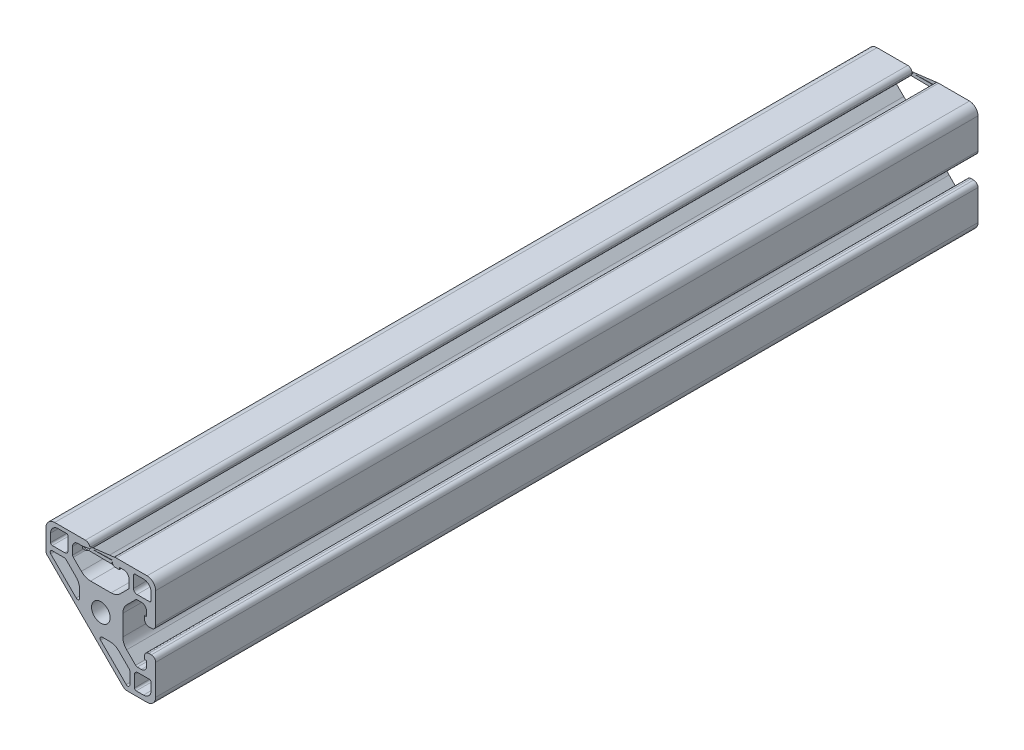
SolidWorks part; units mm, degrees
material "6105-T5 Aluminum"
ref_plane "Front Plane" through (0, 0, 0) normal (0, 0, 1) x (1, 0, 0)
ref_plane "Top Plane" through (0, 0, 0) normal (0, 1, 0) x (1, 0, 0)
ref_plane "Right Plane" through (0, 0, 0) normal (1, 0, 0) x (0, 0, -1)
sketch "Sketch1" plane through (0, 0, 0) normal (0, 0, 1) x (1, 0, 0)
  line L0 (0, 18.0022) -> (0, -18.0022) construction
  line L1 (23.2439, 0) -> (-23.2439, 0) construction
  line L2 (0, 0) -> (21.9293, 21.9293) construction
  line L4 (-22.1966, 22.1966) -> (-17.6741, 17.6741) construction
  line L5 (-17.6741, 17.6741) -> (-22.1966, 22.1966) construction
  line L6 (-17.6741, 17.6741) -> (21.6613, -21.6613) construction
  line L57 (15.55, 18.332) -> (12.565, 18.332)
  line L58 (18.35, 12.8413) -> (18.35, 15.532)
  line L59 (13.205, 12.2693) -> (17.745, 12.2693)
  line L60 (11.935, 17.702) -> (11.935, 13.5393)
  line L61 (12.8993, -18.35) -> (15.55, -18.35)
  line L62 (18.35, -15.55) -> (18.35, -12.8993)
  line L63 (17.72, -12.2693) -> (13.5393, -12.2693)
  line L64 (12.2693, -13.5393) -> (12.2693, -17.72)
  line L65 (10.5703, -17.6313) -> (10.5703, -13.2185)
  line L66 (-0.0445, -8.8513) -> (9.2729, -18.1687)
  line L67 (3.2583, -7.5539) -> (0.4929, -7.5539)
  line L68 (10.3477, -12.6811) -> (6.6079, -8.9413)
  line L69 (-9.0909, 6.7575) -> (-12.7021, 10.3687)
  line L70 (-13.3072, 10.6193) -> (-17.72, 10.6193)
  line L71 (-18.2574, 9.3219) -> (-8.9978, 0.0623)
  line L72 (-7.7004, 0.5997) -> (-7.7004, 3.4003)
  line L73 (-17.695, 12.2693) -> (-13.205, 12.2693)
  line L74 (14.8088, -10.6193) -> (13.3214, -10.6193)
  line L75 (12.6921, -10.3586) -> (9.4306, -7.0971)
  line L76 (8.04, -3.74) -> (8.04, 3.74)
  line L77 (9.4306, 7.0971) -> (12.6921, 10.3586)
  line L78 (13.3214, 10.6193) -> (14.8088, 10.6193)
  line L79 (16.7, 8.7281) -> (16.7, 6.9134)
  line L80 (16.7, 6.9134) -> (15.94, 6.9134)
  line L81 (15.94, 6.9134) -> (15.94, 5.7595)
  line L82 (17.51, 4.1895) -> (18.43, 4.1895)
  line L83 (20, 5.7595) -> (20, 13.0388)
  line L84 (20, 13.0388) -> (20, 16.8689)
  line L85 (16.8881, 20) -> (13.0604, 20)
  line L86 (13.0604, 20) -> (5.6295, 20)
  line L87 (4.06, 18.4701) -> (4.06, 17.5501)
  line L88 (5.63, 16.8567) -> (6.7535, 16.8567)
  line L89 (6.7535, 16.8567) -> (6.7535, 17.6167)
  line L90 (6.7535, 17.6167) -> (8.3698, 17.6167)
  line L91 (10.285, 15.7015) -> (10.285, 12.8154)
  line L92 (10.2371, 12.5705) -> (7.0971, 9.4306)
  line L93 (3.74, 8.04) -> (-3.74, 8.04)
  line L94 (-7.0971, 9.4306) -> (-10.0289, 12.3623)
  line L95 (-10.285, 12.9807) -> (-10.285, 15.7015)
  line L96 (-8.3698, 17.6167) -> (-6.7535, 17.6167)
  line L97 (-6.7535, 17.6167) -> (-6.7535, 16.8567)
  line L98 (-6.7535, 16.8567) -> (-5.63, 16.8567)
  line L99 (-4.06, 18.4267) -> (-4.06, 18.4153)
  line L100 (-5.6299, 20) -> (-12.9742, 20)
  line L101 (-12.9742, 20) -> (-16.83, 20)
  line L102 (-20, 16.83) -> (-20, 9.3524)
  line L103 (-19.5607, 8.2917) -> (8.2917, -19.5607)
  line L104 (9.3524, -20) -> (16.83, -20)
  line L105 (20, -16.83) -> (20, -12.9599)
  line L106 (20, -12.9599) -> (20, -5.7595)
  line L107 (18.43, -4.1895) -> (17.51, -4.1895)
  line L108 (15.94, -5.7595) -> (15.94, -6.9134)
  line L109 (15.94, -6.9134) -> (16.7, -6.9134)
  line L110 (16.7, -6.9134) -> (16.7, -8.7281)
  line L111 (-18.325, 15.8793) -> (-18.325, 12.8993)
  line L112 (-12.565, 18.6793) -> (-15.525, 18.6793)
  line L113 (-11.935, 13.5393) -> (-11.935, 18.0493)
  circle A46 centre (0, 0) radius 3.4
  arc A47 (12.565, 18.332) -> (11.935, 17.702) centre (12.565, 17.702) ccw
  arc A48 (18.35, 15.532) -> (15.55, 18.332) centre (15.55, 15.532) ccw
  arc A49 (17.745, 12.2693) -> (18.35, 12.8413) centre (17.7226, 12.8989) ccw
  arc A50 (11.935, 13.5393) -> (13.205, 12.2693) centre (13.205, 13.5393) ccw
  arc A51 (12.2693, -17.72) -> (12.8993, -18.35) centre (12.8993, -17.72) ccw
  arc A52 (15.55, -18.35) -> (18.35, -15.55) centre (15.55, -15.55) ccw
  arc A53 (18.35, -12.8993) -> (17.72, -12.2693) centre (17.72, -12.8993) ccw
  arc A54 (13.5393, -12.2693) -> (12.2693, -13.5393) centre (13.5393, -13.5393) ccw
  arc A55 (10.5703, -13.2185) -> (10.3477, -12.6811) centre (9.8103, -13.2185) ccw
  arc A56 (9.2729, -18.1687) -> (10.5703, -17.6313) centre (9.8103, -17.6313) ccw
  arc A57 (0.4929, -7.5539) -> (-0.0445, -8.8513) centre (0.4929, -8.3139) ccw
  arc A58 (12.6921, -10.3586) -> (13.3214, -10.6193) centre (13.3214, -9.7293) ccw
  arc A59 (8.04, -3.74) -> (9.4306, -7.0971) centre (12.7878, -3.74) ccw
  arc A60 (9.4306, 7.0971) -> (8.04, 3.74) centre (12.7878, 3.74) ccw
  arc A61 (13.3214, 10.6193) -> (12.6921, 10.3586) centre (13.3214, 9.7293) ccw
  arc A62 (16.7, 8.7281) -> (14.8088, 10.6193) centre (14.8088, 8.7281) ccw
  arc A63 (15.94, 5.7595) -> (17.51, 4.1895) centre (17.51, 5.7595) ccw
  arc A64 (18.43, 4.1895) -> (20, 5.7595) centre (18.43, 5.7595) ccw
  arc A65 (20, 16.8689) -> (16.8881, 20) centre (16.8302, 16.8305) ccw
  arc A66 (5.6295, 20) -> (4.06, 18.4701) centre (5.6295, 18.43) ccw
  arc A67 (4.06, 17.5501) -> (5.63, 16.8567) centre (5.3762, 18.406) ccw
  arc A68 (10.285, 15.7015) -> (8.3698, 17.6167) centre (8.3698, 15.7015) ccw
  arc A69 (10.2371, 12.5705) -> (10.285, 12.8154) centre (9.6352, 12.8154) ccw
  arc A70 (3.74, 8.04) -> (7.0971, 9.4306) centre (3.74, 12.7878) ccw
  arc A71 (-7.0971, 9.4306) -> (-3.74, 8.04) centre (-3.74, 12.7878) ccw
  arc A72 (-10.285, 12.9807) -> (-10.0289, 12.3623) centre (-9.4106, 12.9807) ccw
  arc A73 (-8.3698, 17.6167) -> (-10.285, 15.7015) centre (-8.3698, 15.7015) ccw
  arc A74 (-5.63, 16.8567) -> (-4.06, 18.4267) centre (-5.63, 18.4267) ccw
  arc A75 (-4.06, 18.4153) -> (-5.6299, 20) centre (-5.6299, 18.43) ccw
  arc A76 (-16.83, 20) -> (-20, 16.83) centre (-16.83, 16.83) ccw
  arc A77 (-20, 9.3524) -> (-19.5607, 8.2917) centre (-18.5, 9.3524) ccw
  arc A78 (8.2917, -19.5607) -> (9.3524, -20) centre (9.3524, -18.5) ccw
  arc A79 (16.83, -20) -> (20, -16.83) centre (16.83, -16.83) ccw
  arc A80 (20, -5.7595) -> (18.43, -4.1895) centre (18.43, -5.7595) ccw
  arc A81 (17.51, -4.1895) -> (15.94, -5.7595) centre (17.51, -5.7595) ccw
  arc A82 (14.8088, -10.6193) -> (16.7, -8.7281) centre (14.8088, -8.7281) ccw
  arc A83 (6.6079, -8.9413) -> (3.2583, -7.5539) centre (3.2583, -12.2908) ccw
  arc A84 (-7.7004, 3.4003) -> (-9.0909, 6.7575) centre (-12.4481, 3.4003) ccw
  arc A85 (-17.72, 10.6193) -> (-18.2574, 9.3219) centre (-17.72, 9.8593) ccw
  arc A86 (-8.9978, 0.0623) -> (-7.7004, 0.5997) centre (-8.4604, 0.5997) ccw
  arc A87 (-12.7021, 10.3687) -> (-13.3072, 10.6193) centre (-13.3072, 9.7636) ccw
  arc A88 (-13.205, 12.2693) -> (-11.935, 13.5393) centre (-13.205, 13.5393) ccw
  arc A89 (-18.325, 12.8993) -> (-17.695, 12.2693) centre (-17.695, 12.8993) ccw
  arc A90 (-15.525, 18.6793) -> (-18.325, 15.8793) centre (-15.525, 15.8793) ccw
  arc A91 (-11.935, 18.0493) -> (-12.565, 18.6793) centre (-12.565, 18.0493) ccw
  dimension "D7" = 6.8
  dimension "D6" = 45
  dimension "D9" = 0.76
  dimension "D13" = 0.76
  dimension "D14" = 0.76
  dimension "D1" = 40
  dimension "D2" = 3.3
  dimension "D3" = 8.12
  dimension "D4" = 20.57
  dimension "D5" = 20
  dimension "D8" = 9.3807
  dimension "D10" = 4.06
  dimension "D11" = 7.9
  dimension "D12" = 1.65
extrude "Extrude1" add sketch "Sketch1" against normal blind 300
